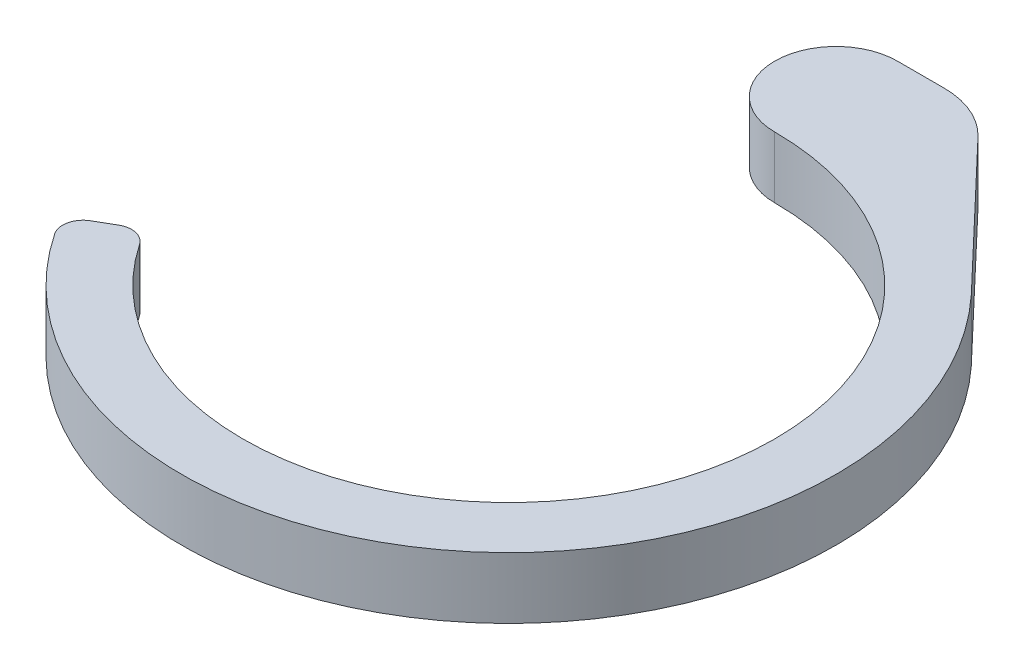
SolidWorks part; units mm, degrees
ref_plane "正面" through (0, 0, 0) normal (0, 0, 1) x (1, 0, 0)
ref_plane "平面" through (0, 0, 0) normal (0, 1, 0) x (1, 0, 0)
ref_plane "右側面" through (0, 0, 0) normal (1, 0, 0) x (0, 0, -1)
sketch "ｽｹｯﾁ2" plane through (0, 0, 0) normal (0, 1, 0) x (1, 0, 0)
  line L1 (-1.8089, 2.6033) -> (0, 0)
  line L2 (-60.4669, -34.9106) -> (-64.8074, -37.4166)
  line L4 (0, 95) -> (11.4274, 95)
  line L5 (25.9115, 88.7917) -> (58.5757, 54.4875)
  arc A0 (-66.4612, -44.5298) -> (57.2894, 55.8384) centre (0, 0) ccw
  arc A1 (-53.8264, -36.4378) -> (0, 65) centre (0, 0) ccw
  arc A2 (0, 95) -> (0, 65) centre (0, 80) ccw
  arc A3 (11.4274, 95) -> (25.9115, 88.7917) centre (11.4274, 75) cw
  arc A4 (-53.8264, -36.4378) -> (-60.4669, -34.9106) centre (-57.9669, -39.2407) ccw
  arc A5 (-66.4612, -44.5298) -> (-64.8074, -37.4166) centre (-62.3074, -41.7467) cw
  dimension "D1" = 160
  dimension "D2" = 130
  dimension "D4" = 20
  dimension "D5" = 5
  dimension "D6" = 5
extrude "ﾎﾞｽ - 押し出し4" add sketch "ｽｹｯﾁ2" along normal blind 15 contours A5 A0 L5 A3 L4 A2 A1 A4 L2
sketch "ｽｹｯﾁ3" plane through (0, 0, 0) normal (0, -1, 0) x (1, 0, 0)
  circle A0 centre (0, -80) radius 10.1
  dimension "D1" = 20.2
extrude "ｶｯﾄ - 押し出し1" cut sketch "ｽｹｯﾁ3" against normal blind 2
